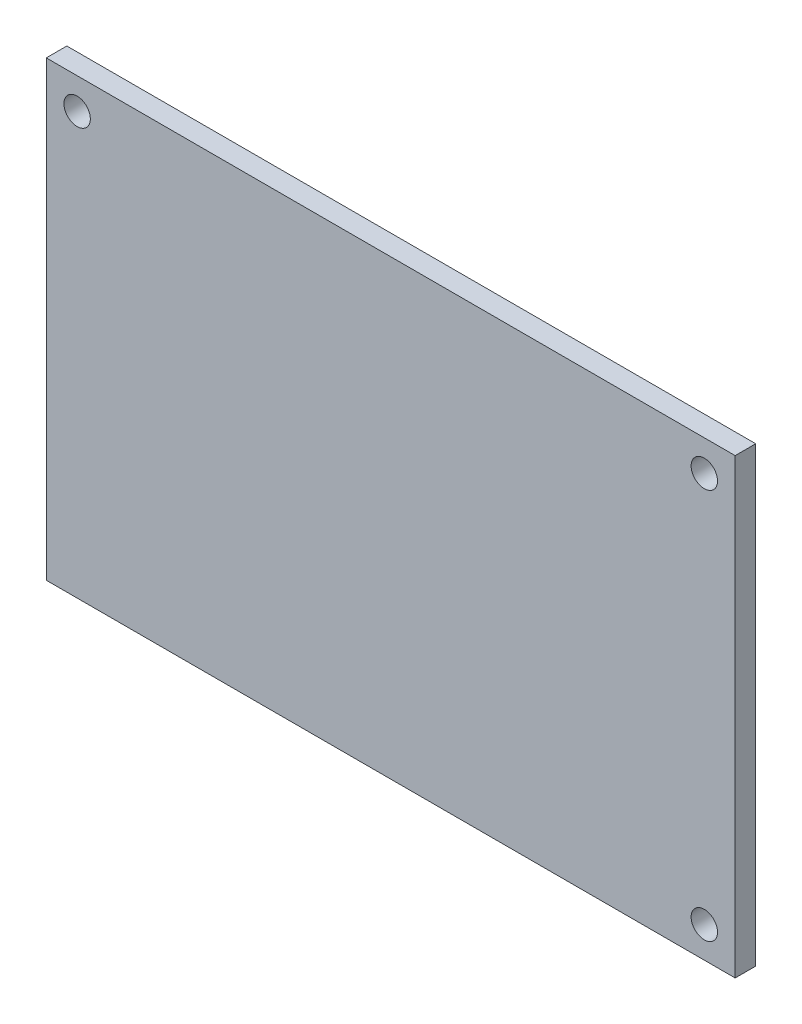
SolidWorks part; units mm, degrees
ref_plane "Front Plane" through (0, 0, 0) normal (0, 0, 1) x (1, 0, 0)
ref_plane "Top Plane" through (0, 0, 0) normal (0, 1, 0) x (1, 0, 0)
ref_plane "Right Plane" through (0, 0, 0) normal (1, 0, 0) x (0, 0, -1)
sketch "Sketch1" plane through (0, 0, 0) normal (0, 0, 1) x (1, 0, 0)
  line L1 (-42.545, 27.94) -> (42.545, 27.94)
  line L2 (-42.545, 27.94) -> (-42.545, -27.94)
  line L3 (-42.545, -27.94) -> (42.545, -27.94)
  line L4 (42.545, 27.94) -> (42.545, -27.94)
  line L5 (-42.545, 27.94) -> (42.545, -27.94) construction
  line L6 (-42.545, -27.94) -> (42.545, 27.94) construction
  point P0 (0, 0)
  dimension "D1" = 55.88
  dimension "D2" = 85.09
extrude "Boss-Extrude1" add sketch "Sketch1" along normal blind 2.54
hole_wizard "#4 Clearance Hole1" positions "Sketch4" profile "Sketch3" hole size "#4" standard "ANSI Inch"
sketch "Sketch4" plane through (0, 0, 2.54) normal (0, 0, 1) x (1, 0, 0)
  line L1 (-38.735, 24.13) -> (38.735, 24.13) construction
  line L2 (-38.735, 24.13) -> (-38.735, -24.13) construction
  line L3 (-38.735, -24.13) -> (38.735, -24.13) construction
  line L4 (38.735, 24.13) -> (38.735, -24.13) construction
  line L5 (-38.735, 24.13) -> (38.735, -24.13) construction
  point P1 (-38.735, 24.13)
  point P2 (38.735, -24.13)
  point P124 (38.735, 24.13)
  dimension "D1" = 77.47
  dimension "D2" = 48.26
sketch "Sketch3" plane through (-38.735, 24.13, 2.54) normal (1, 0, 0) x (0, -1, 0)
  line L0 (0, 0) -> (0, 10.6326)
  line L1 (0, 10.6326) -> (1.6319, 9.652)
  line L2 (1.6319, 9.652) -> (1.6319, 0)
  line L5 (1.6319, 0) -> (0, 0)
  line L10 (0, 10.6326) -> (-1.632, 9.652) construction
  line L11 (0, -6.35) -> (0, 107.95) construction
  dimension "Hole Dia." = 3.2639
  dimension "Hole Depth" = 9.652
  dimension "Drill Angle" = 118
